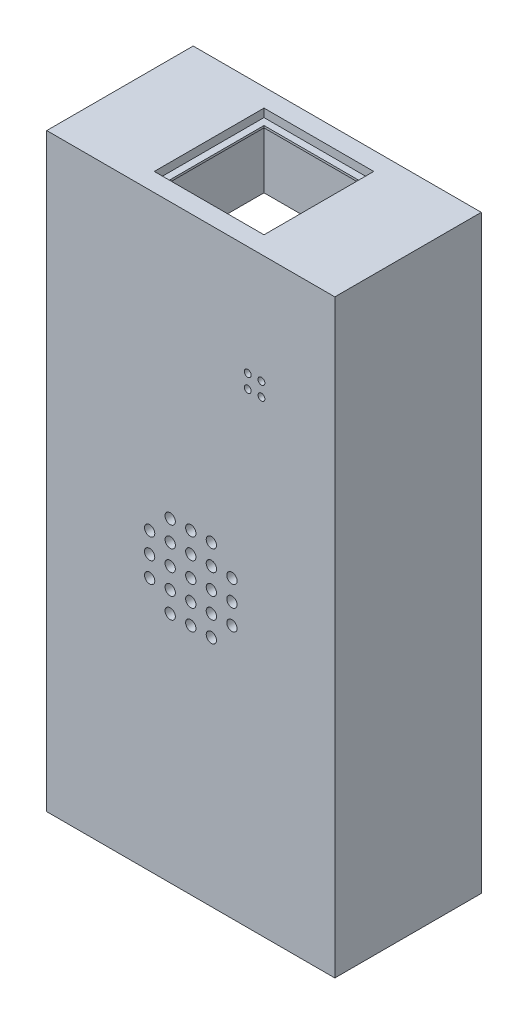
SolidWorks part; units mm, degrees
ref_plane "Front Plane" through (0, 0, 0) normal (0, 0, 1) x (1, 0, 0)
ref_plane "Top Plane" through (0, 0, 0) normal (0, 1, 0) x (1, 0, 0)
ref_plane "Right Plane" through (0, 0, 0) normal (1, 0, 0) x (0, 0, -1)
sketch "身体外形_草图" plane through (0, 0, 0) normal (0, 0, 1) x (1, 0, 0)
  line L1 (-6, -75) -> (36, -75)
  line L2 (-6, -75) -> (-6, 11)
  line L3 (-6, 11) -> (36, 11)
  line L4 (36, -75) -> (36, 11)
  dimension "D1" = 42
  dimension "D2" = 86
extrude "身体外形" add sketch "身体外形_草图" along normal blind 15 and the other way blind 6.35
ref_plane "背板安装面" through (0, 0, -4.35) normal (0, 0, 1) x (1, 0, 0)
sketch "背板沉台_草图" plane through (0, 0, -4.35) normal (0, 0, 1) x (1, 0, 0)
  line L1 (-4.2, -54.2) -> (34.2, -54.2)
  line L2 (-4.2, -54.2) -> (-4.2, 4.2)
  line L3 (-4.2, 4.2) -> (34.2, 4.2)
  line L4 (34.2, -54.2) -> (34.2, 4.2)
  dimension "D1" = 38.4
  dimension "D2" = 58.4
extrude "背板沉台" cut sketch "背板沉台_草图" against normal through all
sketch "PCB腔_草图" plane through (0, 0, -4.35) normal (0, 0, 1) x (1, 0, 0)
  line L1 (-0.5, -50.5) -> (30.5, -50.5)
  line L2 (-0.5, -50.5) -> (-0.5, 0.5)
  line L3 (-0.5, 0.5) -> (30.5, 0.5)
  line L4 (30.5, -50.5) -> (30.5, 0.5)
  dimension "D1" = 31
  dimension "D2" = 51
extrude "PCB腔" cut sketch "PCB腔_草图" along normal blind 17.35
sketch "螺丝底孔x4_草图" plane through (0, 0, -4.35) normal (0, 0, 1) x (1, 0, 0)
  circle A0 centre (-2, 2) radius 0.8
  circle A1 centre (32, 2) radius 0.8
  circle A2 centre (-2, -52) radius 0.8
  circle A3 centre (32, -52) radius 0.8
  dimension "D1" = 1.6
extrude "螺丝底孔x4" cut sketch "螺丝底孔x4_草图" along normal blind 6
ref_plane "身体顶面" through (0, 11, 0) normal (0, 1, 0) x (1, 0, 0)
sketch "轴体沉台_草图" plane through (0, 11, 0) normal (0, 1, 0) x (1, 0, 0)
  line L1 (7, 3.675) -> (23, 3.675)
  line L2 (7, 3.675) -> (7, -12.325)
  line L3 (7, -12.325) -> (23, -12.325)
  line L4 (23, 3.675) -> (23, -12.325)
  dimension "D1" = 16
  dimension "D2" = 16
extrude "轴体沉台" cut sketch "轴体沉台_草图" against normal blind 1.2
sketch "轴体卡孔_草图" plane through (0, 11, 0) normal (0, 1, 0) x (1, 0, 0)
  line L1 (8, 2.675) -> (22, 2.675)
  line L2 (8, 2.675) -> (8, -11.325)
  line L3 (8, -11.325) -> (22, -11.325)
  line L4 (22, 2.675) -> (22, -11.325)
  dimension "D1" = 14
  dimension "D2" = 14
extrude "轴体卡孔" cut sketch "轴体卡孔_草图" against normal blind 1.5
ref_plane "轴体腔顶面" through (0, 9.5, 0) normal (0, 1, 0) x (1, 0, 0)
sketch "轴体腔_走线通道_草图" plane through (0, 9.5, 0) normal (0, 1, 0) x (1, 0, 0)
  line L1 (7.2, 3.475) -> (22.8, 3.475)
  line L2 (7.2, 3.475) -> (7.2, -12.125)
  line L3 (7.2, -12.125) -> (22.8, -12.125)
  line L4 (22.8, 3.475) -> (22.8, -12.125)
  dimension "D1" = 15.6
  dimension "D2" = 15.6
extrude "轴体腔_走线通道" cut sketch "轴体腔_走线通道_草图" against normal blind 9.5
ref_plane "身体正面" through (0, 0, 15) normal (0, 0, 1) x (1, 0, 0)
sketch "扬声器出声孔_草图" plane through (0, 0, 15) normal (0, 0, 1) x (1, 0, 0)
  circle A0 centre (9, -38) radius 0.75
  circle A1 centre (9, -35) radius 0.75
  circle A2 centre (9, -32) radius 0.75
  circle A3 centre (12, -41) radius 0.75
  circle A4 centre (12, -38) radius 0.75
  circle A5 centre (12, -35) radius 0.75
  circle A6 centre (12, -32) radius 0.75
  circle A7 centre (12, -29) radius 0.75
  circle A8 centre (15, -41) radius 0.75
  circle A9 centre (15, -38) radius 0.75
  circle A10 centre (15, -35) radius 0.75
  circle A11 centre (15, -32) radius 0.75
  circle A12 centre (15, -29) radius 0.75
  circle A13 centre (18, -41) radius 0.75
  circle A14 centre (18, -38) radius 0.75
  circle A15 centre (18, -35) radius 0.75
  circle A16 centre (18, -32) radius 0.75
  circle A17 centre (18, -29) radius 0.75
  circle A18 centre (21, -38) radius 0.75
  circle A19 centre (21, -35) radius 0.75
  circle A20 centre (21, -32) radius 0.75
  dimension "D1" = 1.5
extrude "扬声器出声孔" cut sketch "扬声器出声孔_草图" against normal blind 2
sketch "麦克风进声孔_草图" plane through (0, 0, 15) normal (0, 0, 1) x (1, 0, 0)
  circle A0 centre (23.3, -7) radius 0.5
  circle A1 centre (23.3, -5) radius 0.5
  circle A2 centre (25.3, -7) radius 0.5
  circle A3 centre (25.3, -5) radius 0.5
  dimension "D1" = 1
extrude "麦克风进声孔" cut sketch "麦克风进声孔_草图" against normal blind 2
ref_plane "刻字面" through (0, 0, -6.35) normal (0, 0, 1) x (1, 0, 0)
sketch "刻字_身体_草图" plane through (0, 0, -6.35) normal (0, 0, 1) x (1, 0, 0)
  line L0 (27.1213, -65.4918) -> (25.7139, -65.4918)
  line L1 (25.7139, -65.4918) -> (25.7139, -59.7163)
  line L2 (25.7139, -59.7163) -> (23.0384, -59.7163)
  line L3 (23.0384, -59.7163) -> (22.4499, -58.6)
  line L4 (22.4499, -58.6) -> (22.0903, -58.6364)
  line L5 (22.0903, -58.6364) -> (21.7476, -58.6728)
  line L6 (21.7476, -58.6728) -> (21.4216, -58.7092)
  line L7 (21.4216, -58.7092) -> (21.1126, -58.7456)
  line L8 (21.1126, -58.7456) -> (20.8204, -58.782)
  line L9 (20.8204, -58.782) -> (20.545, -58.8184)
  line L10 (20.545, -58.8184) -> (21.1274, -59.7163)
  line L11 (21.1274, -59.7163) -> (17.0263, -59.7163)
  line L12 (17.0263, -59.7163) -> (17.0263, -64.6425)
  line L13 (17.0263, -64.6425) -> (16.8618, -64.5124)
  line L14 (16.8618, -64.5124) -> (16.7, -64.3809)
  line L15 (16.7, -64.3809) -> (16.541, -64.2481)
  line L16 (16.541, -64.2481) -> (16.3846, -64.114)
  line L17 (16.3846, -64.114) -> (16.2309, -63.9785)
  line L18 (16.2309, -63.9785) -> (16.0799, -63.8417)
  line L19 (16.0799, -63.8417) -> (15.0607, -64.9822)
  line L20 (15.0607, -64.9822) -> (15.368, -65.2311)
  line L21 (15.368, -65.2311) -> (15.6835, -65.4763)
  line L22 (15.6835, -65.4763) -> (16.0071, -65.7178)
  line L23 (16.0071, -65.7178) -> (16.3387, -65.9556)
  line L24 (16.3387, -65.9556) -> (16.6785, -66.1897)
  line L25 (16.6785, -66.1897) -> (17.0263, -66.42)
  line L26 (17.0263, -66.42) -> (17.0263, -68.513)
  line L27 (17.0263, -68.513) -> (17.0768, -69.118)
  line L28 (17.0768, -69.118) -> (17.2285, -69.6145)
  line L29 (17.2285, -69.6145) -> (17.4813, -70.0024)
  line L30 (17.4813, -70.0024) -> (17.8352, -70.2818)
  line L31 (17.8352, -70.2818) -> (18.2902, -70.4527)
  line L32 (18.2902, -70.4527) -> (18.8463, -70.5151)
  line L33 (18.8463, -70.5151) -> (20.8969, -70.5151)
  line L34 (20.8969, -70.5151) -> (20.9518, -70.1817)
  line L35 (20.9518, -70.1817) -> (21.0034, -69.8774)
  line L36 (21.0034, -69.8774) -> (21.0516, -69.602)
  line L37 (21.0516, -69.602) -> (21.0964, -69.3556)
  line L38 (21.0964, -69.3556) -> (21.1378, -69.1383)
  line L39 (21.1378, -69.1383) -> (21.1759, -68.9498)
  line L40 (21.1759, -68.9498) -> (20.8895, -68.9684)
  line L41 (20.8895, -68.9684) -> (20.5962, -68.9836)
  line L42 (20.5962, -68.9836) -> (20.2963, -68.9953)
  line L43 (20.2963, -68.9953) -> (19.9896, -69.0038)
  line L44 (19.9896, -69.0038) -> (19.6761, -69.0088)
  line L45 (19.6761, -69.0088) -> (19.3559, -69.0105)
  line L46 (19.3559, -69.0105) -> (19.1483, -68.9916)
  line L47 (19.1483, -68.9916) -> (18.9784, -68.935)
  line L48 (18.9784, -68.935) -> (18.8463, -68.8406)
  line L49 (18.8463, -68.8406) -> (18.7519, -68.7085)
  line L50 (18.7519, -68.7085) -> (18.6953, -68.5387)
  line L51 (18.6953, -68.5387) -> (18.6764, -68.331)
  line L52 (18.6764, -68.331) -> (18.6764, -67.3968)
  line L53 (18.6764, -67.3968) -> (19.7988, -67.9704)
  line L54 (19.7988, -67.9704) -> (20.9858, -68.5144)
  line L55 (20.9858, -68.5144) -> (22.2376, -69.0287)
  line L56 (22.2376, -69.0287) -> (23.5541, -69.5134)
  line L57 (23.5541, -69.5134) -> (24.9353, -69.9684)
  line L58 (24.9353, -69.9684) -> (26.3812, -70.3937)
  line L59 (26.3812, -70.3937) -> (26.544, -70.052)
  line L60 (26.544, -70.052) -> (26.7007, -69.7385)
  line L61 (26.7007, -69.7385) -> (26.8514, -69.4534)
  line L62 (26.8514, -69.4534) -> (26.996, -69.1966)
  line L63 (26.996, -69.1966) -> (27.1345, -68.968)
  line L64 (27.1345, -68.968) -> (27.2669, -68.7678)
  line L65 (27.2669, -68.7678) -> (26.1166, -68.5319)
  line L66 (26.1166, -68.5319) -> (25.0115, -68.269)
  line L67 (25.0115, -68.269) -> (23.9515, -67.9792)
  line L68 (23.9515, -67.9792) -> (22.9366, -67.6624)
  line L69 (22.9366, -67.6624) -> (21.967, -67.3186)
  line L70 (21.967, -67.3186) -> (21.0425, -66.9478)
  line L71 (21.0425, -66.9478) -> (27.1213, -66.9478)
  line L72 (27.1213, -66.9478) -> (27.1213, -65.4918)
  line L73 (18.6764, -61.148) -> (24.0637, -61.148)
  line L74 (24.0637, -61.148) -> (24.0637, -61.876)
  line L75 (24.0637, -61.876) -> (18.6764, -61.876)
  line L76 (18.6764, -61.876) -> (18.6764, -61.148)
  line L77 (24.0637, -63.6718) -> (18.6764, -63.6718)
  line L78 (18.6764, -63.6718) -> (18.6764, -62.9438)
  line L79 (18.6764, -62.9438) -> (24.0637, -62.9438)
  line L80 (24.0637, -62.9438) -> (24.0637, -63.6718)
  line L81 (24.0637, -65.4918) -> (18.6764, -65.4918)
  line L82 (18.6764, -65.4918) -> (18.6764, -64.7395)
  line L83 (18.6764, -64.7395) -> (24.0637, -64.7395)
  line L84 (24.0637, -64.7395) -> (24.0637, -65.4918)
  line L85 (12.8524, -58.6607) -> (11.2872, -59.0611)
  line L86 (11.2872, -59.0611) -> (11.4247, -59.5729)
  line L87 (11.4247, -59.5729) -> (11.5662, -60.0729)
  line L88 (11.5662, -60.0729) -> (11.7118, -60.5611)
  line L89 (11.7118, -60.5611) -> (11.8615, -61.0375)
  line L90 (11.8615, -61.0375) -> (12.0152, -61.5021)
  line L91 (12.0152, -61.5021) -> (12.1729, -61.9549)
  line L92 (12.1729, -61.9549) -> (12.1729, -66.8872)
  line L93 (12.1729, -66.8872) -> (11.5536, -66.1925)
  line L94 (11.5536, -66.1925) -> (10.9899, -65.4595)
  line L95 (10.9899, -65.4595) -> (10.4818, -64.688)
  line L96 (10.4818, -64.688) -> (10.0293, -63.8781)
  line L97 (10.0293, -63.8781) -> (9.6325, -63.0297)
  line L98 (9.6325, -63.0297) -> (9.2912, -62.143)
  line L99 (9.2912, -62.143) -> (11.4813, -62.143)
  line L100 (11.4813, -62.143) -> (11.4813, -60.6263)
  line L101 (11.4813, -60.6263) -> (8.3145, -60.6263)
  line L102 (8.3145, -60.6263) -> (8.3145, -58.6607)
  line L103 (8.3145, -58.6607) -> (6.7128, -58.6607)
  line L104 (6.7128, -58.6607) -> (6.7128, -60.6263)
  line L105 (6.7128, -60.6263) -> (3.2184, -60.6263)
  line L106 (3.2184, -60.6263) -> (3.2184, -62.143)
  line L107 (3.2184, -62.143) -> (5.8332, -62.143)
  line L108 (5.8332, -62.143) -> (5.4909, -62.9859)
  line L109 (5.4909, -62.9859) -> (5.0789, -63.7958)
  line L110 (5.0789, -63.7958) -> (4.5971, -64.5727)
  line L111 (4.5971, -64.5727) -> (4.0455, -65.3165)
  line L112 (4.0455, -65.3165) -> (3.4242, -66.0274)
  line L113 (3.4242, -66.0274) -> (2.7331, -66.7052)
  line L114 (2.7331, -66.7052) -> (2.9073, -66.9721)
  line L115 (2.9073, -66.9721) -> (3.0822, -67.2471)
  line L116 (3.0822, -67.2471) -> (3.2578, -67.5302)
  line L117 (3.2578, -67.5302) -> (3.4341, -67.8214)
  line L118 (3.4341, -67.8214) -> (3.6111, -68.1207)
  line L119 (3.6111, -68.1207) -> (3.7887, -68.4281)
  line L120 (3.7887, -68.4281) -> (3.9488, -68.2572)
  line L121 (3.9488, -68.2572) -> (4.1055, -68.0803)
  line L122 (4.1055, -68.0803) -> (4.2588, -67.8973)
  line L123 (4.2588, -67.8973) -> (4.4088, -67.7082)
  line L124 (4.4088, -67.7082) -> (4.5554, -67.513)
  line L125 (4.5554, -67.513) -> (4.6987, -67.3118)
  line L126 (4.6987, -67.3118) -> (4.6987, -68.5616)
  line L127 (4.6987, -68.5616) -> (6.7128, -68.5616)
  line L128 (6.7128, -68.5616) -> (6.7128, -70.6)
  line L129 (6.7128, -70.6) -> (8.3145, -70.6)
  line L130 (8.3145, -70.6) -> (8.3145, -68.5616)
  line L131 (8.3145, -68.5616) -> (10.2679, -68.5616)
  line L132 (10.2679, -68.5616) -> (10.2679, -67.2633)
  line L133 (10.2679, -67.2633) -> (10.426, -67.4942)
  line L134 (10.426, -67.4942) -> (10.5888, -67.7217)
  line L135 (10.5888, -67.7217) -> (10.7563, -67.9458)
  line L136 (10.7563, -67.9458) -> (10.9285, -68.1666)
  line L137 (10.9285, -68.1666) -> (11.1055, -68.384)
  line L138 (11.1055, -68.384) -> (11.2872, -68.598)
  line L139 (11.2872, -68.598) -> (11.4112, -68.3979)
  line L140 (11.4112, -68.3979) -> (11.5447, -68.1861)
  line L141 (11.5447, -68.1861) -> (11.6876, -67.9625)
  line L142 (11.6876, -67.9625) -> (11.8399, -67.7271)
  line L143 (11.8399, -67.7271) -> (12.0017, -67.4798)
  line L144 (12.0017, -67.4798) -> (12.1729, -67.2208)
  line L145 (12.1729, -67.2208) -> (12.1729, -70.5757)
  line L146 (12.1729, -70.5757) -> (13.6289, -70.5757)
  line L147 (13.6289, -70.5757) -> (13.6289, -65.237)
  line L148 (13.6289, -65.237) -> (13.759, -65.4669)
  line L149 (13.759, -65.4669) -> (13.8905, -65.6913)
  line L150 (13.8905, -65.6913) -> (14.0233, -65.9104)
  line L151 (14.0233, -65.9104) -> (14.1574, -66.1241)
  line L152 (14.1574, -66.1241) -> (14.2929, -66.3324)
  line L153 (14.2929, -66.3324) -> (14.4297, -66.5353)
  line L154 (14.4297, -66.5353) -> (14.481, -66.1649)
  line L155 (14.481, -66.1649) -> (14.5376, -65.7898)
  line L156 (14.5376, -65.7898) -> (14.5996, -65.4099)
  line L157 (14.5996, -65.4099) -> (14.667, -65.0253)
  line L158 (14.667, -65.0253) -> (14.7398, -64.6361)
  line L159 (14.7398, -64.6361) -> (14.818, -64.2421)
  line L160 (14.818, -64.2421) -> (14.4971, -63.5882)
  line L161 (14.4971, -63.5882) -> (14.1736, -62.8238)
  line L162 (14.1736, -62.8238) -> (13.8473, -61.9488)
  line L163 (13.8473, -61.9488) -> (13.5184, -60.9633)
  line L164 (13.5184, -60.9633) -> (13.1867, -59.8673)
  line L165 (13.1867, -59.8673) -> (12.8524, -58.6607)
  line L166 (10.1163, -67.0328) -> (8.3145, -67.0328)
  line L167 (8.3145, -67.0328) -> (8.3145, -62.8285)
  line L168 (8.3145, -62.8285) -> (8.5263, -63.5874)
  line L169 (8.5263, -63.5874) -> (8.7735, -64.323)
  line L170 (8.7735, -64.323) -> (9.0561, -65.0353)
  line L171 (9.0561, -65.0353) -> (9.3741, -65.7244)
  line L172 (9.3741, -65.7244) -> (9.7275, -66.3902)
  line L173 (9.7275, -66.3902) -> (10.1163, -67.0328)
  line L174 (6.7128, -62.8952) -> (6.7128, -67.0328)
  line L175 (6.7128, -67.0328) -> (4.8868, -67.0328)
  line L176 (4.8868, -67.0328) -> (5.2442, -66.4493)
  line L177 (5.2442, -66.4493) -> (5.5804, -65.8235)
  line L178 (5.5804, -65.8235) -> (5.8953, -65.1551)
  line L179 (5.8953, -65.1551) -> (6.1891, -64.4443)
  line L180 (6.1891, -64.4443) -> (6.4616, -63.691)
  line L181 (6.4616, -63.691) -> (6.7128, -62.8952)
extrude "刻字_身体" cut sketch "刻字_身体_草图" along normal blind 0.3
